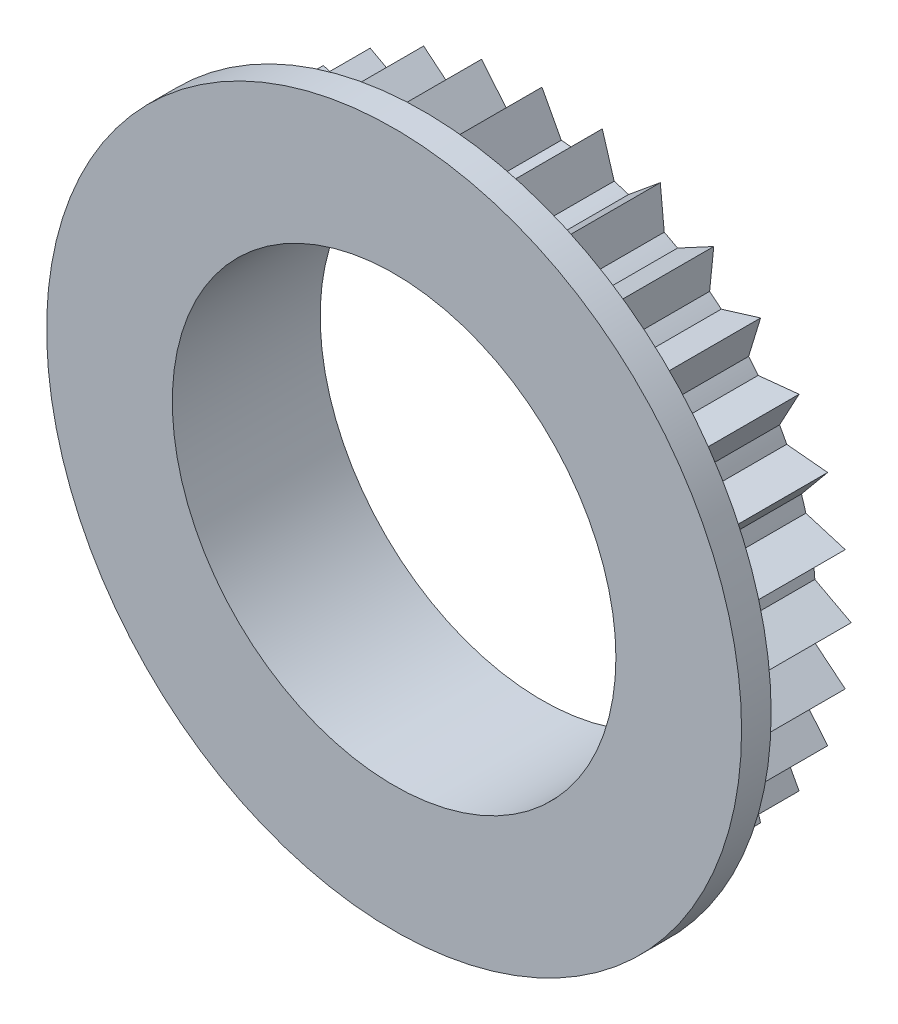
SolidWorks part; units mm, degrees
ref_plane "Front Plane" through (0, 0, 0) normal (0, 0, 1) x (1, 0, 0)
ref_plane "Top Plane" through (0, 0, 0) normal (0, 1, 0) x (1, 0, 0)
ref_plane "Right Plane" through (0, 0, 0) normal (1, 0, 0) x (0, 0, -1)
sketch "Sketch1" plane through (0, 0, 0) normal (0, 0, 1) x (1, 0, 0)
  line L0 (0, 33.2331) -> (0, -49.7016) construction
  line L1 (0, 20.9114) -> (1.3054, 18.4539)
  line L2 (0, 20.9114) -> (-1.3054, 18.4539)
  line L3 (4.0796, 20.5096) -> (4.8805, 17.8446)
  line L4 (4.0796, 20.5096) -> (2.3198, 18.354)
  line L5 (8.0024, 19.3196) -> (8.268, 16.5496)
  line L6 (8.0024, 19.3196) -> (5.8559, 17.5487)
  line L7 (11.6177, 17.3872) -> (11.3378, 14.6186)
  line L8 (11.6177, 17.3872) -> (9.167, 16.0691)
  line L9 (14.7866, 14.7866) -> (13.9719, 12.1258)
  line L10 (14.7866, 14.7866) -> (12.1258, 13.9719)
  line L11 (17.3872, 11.6177) -> (16.0691, 9.167)
  line L12 (17.3872, 11.6177) -> (14.6186, 11.3378)
  line L13 (19.3196, 8.0024) -> (17.5487, 5.8559)
  line L14 (19.3196, 8.0024) -> (16.5496, 8.268)
  line L15 (20.5096, 4.0796) -> (18.354, 2.3198)
  line L16 (20.5096, 4.0796) -> (17.8446, 4.8805)
  line L17 (20.9114, 0) -> (18.4539, -1.3054)
  line L18 (20.9114, 0) -> (18.4539, 1.3054)
  line L19 (20.5096, -4.0796) -> (17.8446, -4.8805)
  line L20 (20.5096, -4.0796) -> (18.354, -2.3198)
  line L21 (19.3196, -8.0024) -> (16.5496, -8.268)
  line L22 (19.3196, -8.0024) -> (17.5487, -5.8559)
  line L23 (17.3872, -11.6177) -> (14.6186, -11.3378)
  line L24 (17.3872, -11.6177) -> (16.0691, -9.167)
  line L25 (14.7866, -14.7866) -> (12.1258, -13.9719)
  line L26 (14.7866, -14.7866) -> (13.9719, -12.1258)
  line L27 (11.6177, -17.3872) -> (9.167, -16.0691)
  line L28 (11.6177, -17.3872) -> (11.3378, -14.6186)
  line L29 (8.0024, -19.3196) -> (5.8559, -17.5487)
  line L30 (8.0024, -19.3196) -> (8.268, -16.5496)
  line L31 (4.0796, -20.5096) -> (2.3198, -18.354)
  line L32 (4.0796, -20.5096) -> (4.8805, -17.8446)
  line L33 (0, -20.9114) -> (-1.3054, -18.4539)
  line L34 (0, -20.9114) -> (1.3054, -18.4539)
  line L35 (-4.0796, -20.5096) -> (-4.8805, -17.8446)
  line L36 (-4.0796, -20.5096) -> (-2.3198, -18.354)
  line L37 (-8.0024, -19.3196) -> (-8.268, -16.5496)
  line L38 (-8.0024, -19.3196) -> (-5.8559, -17.5487)
  line L39 (-11.6177, -17.3872) -> (-11.3378, -14.6186)
  line L40 (-11.6177, -17.3872) -> (-9.167, -16.0691)
  line L41 (-14.7866, -14.7866) -> (-13.9719, -12.1258)
  line L42 (-14.7866, -14.7866) -> (-12.1258, -13.9719)
  line L43 (-17.3872, -11.6177) -> (-16.0691, -9.167)
  line L44 (-17.3872, -11.6177) -> (-14.6186, -11.3378)
  line L45 (-19.3196, -8.0024) -> (-17.5487, -5.8559)
  line L46 (-19.3196, -8.0024) -> (-16.5496, -8.268)
  line L47 (-20.5096, -4.0796) -> (-18.354, -2.3198)
  line L48 (-20.5096, -4.0796) -> (-17.8446, -4.8805)
  line L49 (-20.9114, 0) -> (-18.4539, 1.3054)
  line L50 (-20.9114, 0) -> (-18.4539, -1.3054)
  line L51 (-20.5096, 4.0796) -> (-17.8446, 4.8805)
  line L52 (-20.5096, 4.0796) -> (-18.354, 2.3198)
  line L53 (-19.3196, 8.0024) -> (-16.5496, 8.268)
  line L54 (-19.3196, 8.0024) -> (-17.5487, 5.8559)
  line L55 (-17.3872, 11.6177) -> (-14.6186, 11.3378)
  line L56 (-17.3872, 11.6177) -> (-16.0691, 9.167)
  line L57 (-14.7866, 14.7866) -> (-12.1258, 13.9719)
  line L58 (-14.7866, 14.7866) -> (-13.9719, 12.1258)
  line L59 (-11.6177, 17.3872) -> (-9.167, 16.0691)
  line L60 (-11.6177, 17.3872) -> (-11.3378, 14.6186)
  line L61 (-8.0024, 19.3196) -> (-5.8559, 17.5487)
  line L62 (-8.0024, 19.3196) -> (-8.268, 16.5496)
  line L63 (-4.0796, 20.5096) -> (-2.3198, 18.354)
  line L64 (-4.0796, 20.5096) -> (-4.8805, 17.8446)
  circle A0 centre (0, 0) radius 23.5
  circle A1 centre (0, 0) radius 15
  arc A2 (-16.0691, 9.167) -> (-16.5496, 8.268) centre (0, 0) ccw
  arc A3 (-13.9719, 12.1258) -> (-14.6186, 11.3378) centre (0, 0) ccw
  arc A4 (-11.3378, 14.6186) -> (-12.1258, 13.9719) centre (0, 0) ccw
  arc A5 (-8.268, 16.5496) -> (-9.167, 16.0691) centre (0, 0) ccw
  arc A6 (-4.8805, 17.8446) -> (-5.8559, 17.5487) centre (0, 0) ccw
  arc A7 (-1.3054, 18.4539) -> (-2.3198, 18.354) centre (0, 0) ccw
  arc A8 (2.3198, 18.354) -> (1.3054, 18.4539) centre (0, 0) ccw
  arc A9 (5.8559, 17.5487) -> (4.8805, 17.8446) centre (0, 0) ccw
  arc A10 (9.167, 16.0691) -> (8.268, 16.5496) centre (0, 0) ccw
  arc A11 (12.1258, 13.9719) -> (11.3378, 14.6186) centre (0, 0) ccw
  arc A12 (14.6186, 11.3378) -> (13.9719, 12.1258) centre (0, 0) ccw
  arc A13 (16.5496, 8.268) -> (16.0691, 9.167) centre (0, 0) ccw
  arc A14 (17.8446, 4.8805) -> (17.5487, 5.8559) centre (0, 0) ccw
  arc A15 (18.4539, 1.3054) -> (18.354, 2.3198) centre (0, 0) ccw
  arc A16 (18.354, -2.3198) -> (18.4539, -1.3054) centre (0, 0) ccw
  arc A17 (17.5487, -5.8559) -> (17.8446, -4.8805) centre (0, 0) ccw
  arc A18 (16.0691, -9.167) -> (16.5496, -8.268) centre (0, 0) ccw
  arc A19 (13.9719, -12.1258) -> (14.6186, -11.3378) centre (0, 0) ccw
  arc A20 (11.3378, -14.6186) -> (12.1258, -13.9719) centre (0, 0) ccw
  arc A21 (8.268, -16.5496) -> (9.167, -16.0691) centre (0, 0) ccw
  arc A22 (4.8805, -17.8446) -> (5.8559, -17.5487) centre (0, 0) ccw
  arc A23 (1.3054, -18.4539) -> (2.3198, -18.354) centre (0, 0) ccw
  arc A24 (-2.3198, -18.354) -> (-1.3054, -18.4539) centre (0, 0) ccw
  arc A25 (-5.8559, -17.5487) -> (-4.8805, -17.8446) centre (0, 0) ccw
  arc A26 (-9.167, -16.0691) -> (-8.268, -16.5496) centre (0, 0) ccw
  arc A27 (-12.1258, -13.9719) -> (-11.3378, -14.6186) centre (0, 0) ccw
  arc A28 (-14.6186, -11.3378) -> (-13.9719, -12.1258) centre (0, 0) ccw
  arc A29 (-16.5496, -8.268) -> (-16.0691, -9.167) centre (0, 0) ccw
  arc A30 (-17.8446, -4.8805) -> (-17.5487, -5.8559) centre (0, 0) ccw
  arc A31 (-18.4539, -1.3054) -> (-18.354, -2.3198) centre (0, 0) ccw
  arc A32 (-18.354, 2.3198) -> (-18.4539, 1.3054) centre (0, 0) ccw
  arc A33 (-17.5487, 5.8559) -> (-17.8446, 4.8805) centre (0, 0) ccw
  point P4 (0, 0)
  point P105 (0, 0)
  dimension "D1" = 47
  dimension "D2" = 30
  dimension "D3" = 37
  dimension "D4" = 32
extrude "Boss-Extrude1" add sketch "Sketch1" along normal blind 8 contours L56 A2 L53 L54 A33 L51 L52 A32 L49 L50 A31 L47 L48 A30 L45 L46 A29 L43 L44 A28 L41 L42 A27 L39 L40 A26 L37 L38 A25 L35 L36 A24 L33 L34 A23 L31 L32 A22 L29 L30 A21 L27 L28 A20 L25 L26 A19 L23 L24 A18 L21 L22 A17 L19 L20 A16 L17 L18 A15 L15 L16 A14 L13 L14 A13 L11 L12 A12 L9 L10 A11 L7 L8 A10 L5 L6 A9 L3 L4 A8 L1 L2 A7 L63 L64 A6 L61 L62 A5 L59 L60 A4 L57 L58 A3 L55
sketch "Sketch2" plane through (0, 0, 0) normal (0, 0, -1) x (-1, 0, 0)
sketch "Sketch3" plane through (0, 0, 8) normal (0, 0, 1) x (1, 0, 0)
  circle A0 centre (0, 0) radius 23.5
  dimension "D1" = 47
extrude "Boss-Extrude2" add sketch "Sketch3" along normal blind 2
sketch "Sketch5" plane through (0, 0, 10) normal (0, 0, 1) x (1, 0, 0)
  circle A0 centre (0, 0) radius 15
  dimension "D1" = 30
extrude "Cut-Extrude2" cut sketch "Sketch5" against normal blind 12
